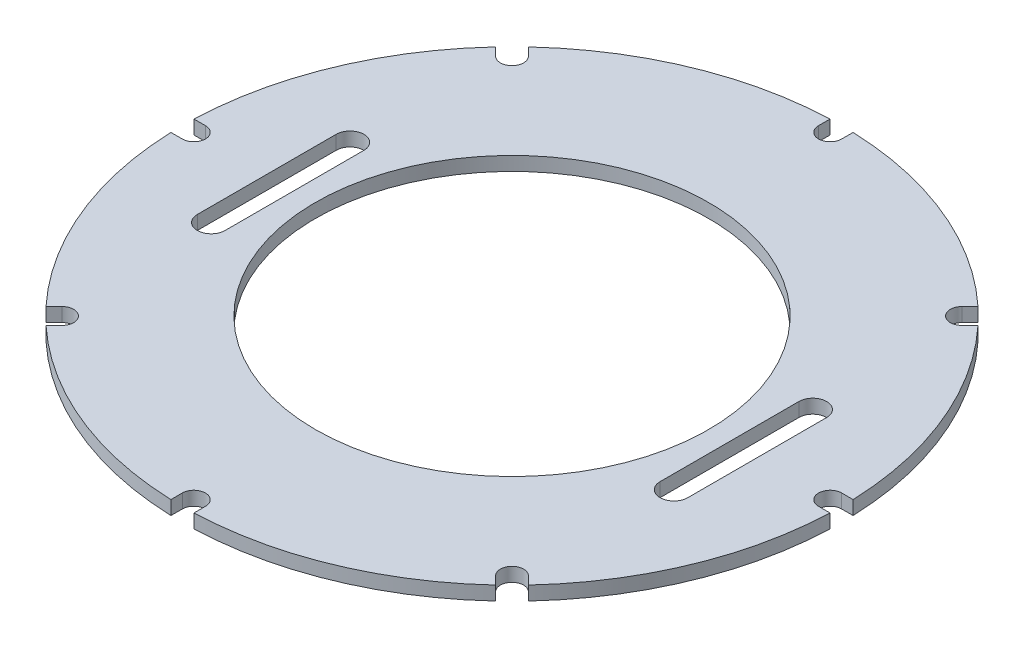
SolidWorks part; units mm, degrees
ref_plane "Front Plane" through (0, 0, 0) normal (0, 0, 1) x (1, 0, 0)
ref_plane "Top Plane" through (0, 0, 0) normal (0, 1, 0) x (1, 0, 0)
ref_plane "Right Plane" through (0, 0, 0) normal (1, 0, 0) x (0, 0, -1)
sketch "Sketch1" plane through (0, 0, 0) normal (0, 1, 0) x (1, 0, 0)
  line L0 (10, -3) -> (10, 3) construction
  line L1 (9.4, -3) -> (9.4, 3)
  line L2 (10.6, -3) -> (10.6, 3)
  line L3 (0, 0) -> (0, -14.25) construction
  line L4 (-10, -3) -> (-10, 3) construction
  line L5 (-9.4, -3) -> (-9.4, 3)
  line L6 (-10.6, -3) -> (-10.6, 3)
  line L7 (-0.5, -13.75) -> (-0.5, -14.2412)
  line L8 (0.5, -13.75) -> (0.5, -14.2412)
  line L9 (-10.0763, -9.3692) -> (-10.4236, -9.7165)
  line L10 (-9.3692, -10.0763) -> (-9.7165, -10.4236)
  line L11 (-13.75, 0.5) -> (-14.2412, 0.5)
  line L12 (-13.75, -0.5) -> (-14.2412, -0.5)
  line L13 (-9.3692, 10.0763) -> (-9.7165, 10.4236)
  line L14 (-10.0763, 9.3692) -> (-10.4236, 9.7165)
  line L15 (0.5, 13.75) -> (0.5, 14.2412)
  line L16 (-0.5, 13.75) -> (-0.5, 14.2412)
  line L17 (10.0763, 9.3692) -> (10.4236, 9.7165)
  line L18 (9.3692, 10.0763) -> (9.7165, 10.4236)
  line L19 (13.75, -0.5) -> (14.2412, -0.5)
  line L20 (13.75, 0.5) -> (14.2412, 0.5)
  line L21 (9.3692, -10.0763) -> (9.7165, -10.4236)
  line L22 (10.0763, -9.3692) -> (10.4236, -9.7165)
  circle A0 centre (0, 0) radius 14.25
  circle A1 centre (0, 0) radius 8.5
  arc A2 (9.4, -3) -> (10.6, -3) centre (10, -3) ccw
  arc A3 (10.6, 3) -> (9.4, 3) centre (10, 3) ccw
  arc A4 (-9.4, -3) -> (-10.6, -3) centre (-10, -3) cw
  arc A5 (-10.6, 3) -> (-9.4, 3) centre (-10, 3) cw
  arc A6 (0.5, -13.75) -> (-0.5, -13.75) centre (0, -13.75) ccw
  arc A7 (-9.3692, -10.0763) -> (-10.0763, -9.3692) centre (-9.7227, -9.7227) ccw
  arc A8 (-13.75, -0.5) -> (-13.75, 0.5) centre (-13.75, 0) ccw
  arc A9 (-10.0763, 9.3692) -> (-9.3692, 10.0763) centre (-9.7227, 9.7227) ccw
  arc A10 (-0.5, 13.75) -> (0.5, 13.75) centre (0, 13.75) ccw
  arc A11 (9.3692, 10.0763) -> (10.0763, 9.3692) centre (9.7227, 9.7227) ccw
  arc A12 (13.75, 0.5) -> (13.75, -0.5) centre (13.75, 0) ccw
  arc A13 (10.0763, -9.3692) -> (9.3692, -10.0763) centre (9.7227, -9.7227) ccw
  point P6 (10, 0)
  point P13 (-10, 0)
  point P61 (0, 0)
  dimension "D1" = 28.5
  dimension "D2" = 17
  dimension "D6" = 8
  dimension "D3" = 1.2
  dimension "D4" = 6
  dimension "D5" = 10
extrude "Boss-Extrude1" add sketch "Sketch1" along normal blind 0.6 contours A13 L22 A0 L19 A12 L20 L17 A11 L18 L15 A10 L16 L13 A9 L14 L11 A8 L12 L9 A7 L10 L7 A6 L8 L21 A3 L2 A2 L1 A1 L6 A5 L5 A4
